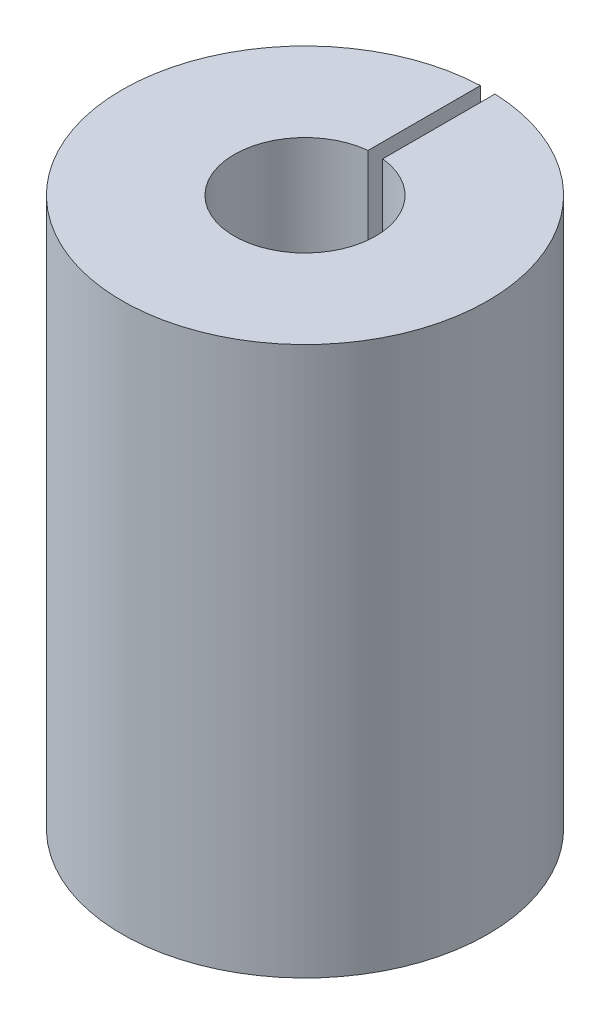
SolidWorks part; units mm, degrees
ref_plane "Front Plane" through (0, 0, 0) normal (0, 0, 1) x (1, 0, 0)
ref_plane "Top Plane" through (0, 0, 0) normal (0, 1, 0) x (1, 0, 0)
ref_plane "Right Plane" through (0, 0, 0) normal (1, 0, 0) x (0, 0, -1)
sketch "Sketch1" plane through (0, 0, 0) normal (0, 1, 0) x (1, 0, 0)
  circle A0 centre (-18.1756, 4.2341) radius 6.35
  dimension "D1" = 12.7
extrude "Boss-Extrude1" add sketch "Sketch1" along normal blind 19.05
hole_wizard "#10 (0.1935) Diameter Hole2" positions "Sketch4" profile "Sketch5" hole size "#10" standard "ANSI Inch" end condition through all
sketch "Sketch4" plane through (0, 19.05, 0) normal (0, 1, 0) x (1, 0, 0)
  line L0 (-18.1756, 4.2341) -> (-18.1756, 10.5841) construction
  line L2 (-18.1756, 4.2341) -> (-11.8256, 4.2341) construction
  circle A0 centre (-18.1756, 4.2341) radius 6.35 construction
  point P0 (-18.1756, 4.2341)
sketch "Sketch5" plane through (-18.1756, 19.05, -4.2341) normal (1, 0, 0) x (0, 0, 1)
  line L0 (0, 0) -> (0, 19.05)
  line L1 (0, 19.05) -> (2.4574, 19.05)
  line L2 (2.4574, 19.05) -> (2.4574, 0)
  line L5 (2.4574, 0) -> (0, 0)
  line L11 (0, -6.35) -> (0, 107.95) construction
  dimension "Thru Hole Dia." = 4.9149
  dimension "Thru Hole Depth" = 19.05
sketch "Sketch6" plane through (0, 19.05, 0) normal (0, 1, 0) x (1, 0, 0)
  line L0 (-18.1756, 6.6916) -> (-18.1756, 10.5841) construction
  line L3 (-18.4296, 10.5791) -> (-18.4296, 6.6784)
  line L5 (-17.9216, 10.5791) -> (-17.9216, 6.6784)
  arc A0 (-17.9216, 6.6784) -> (-18.4296, 6.6784) centre (-18.1756, 4.2341) ccw
  arc A1 (-17.9216, 10.5791) -> (-18.4296, 10.5791) centre (-18.1756, 4.2341) ccw
  dimension "D1" = 0.254
  dimension "D2" = 0.254
extrude "Cut-Extrude1" cut sketch "Sketch6" against normal through all
